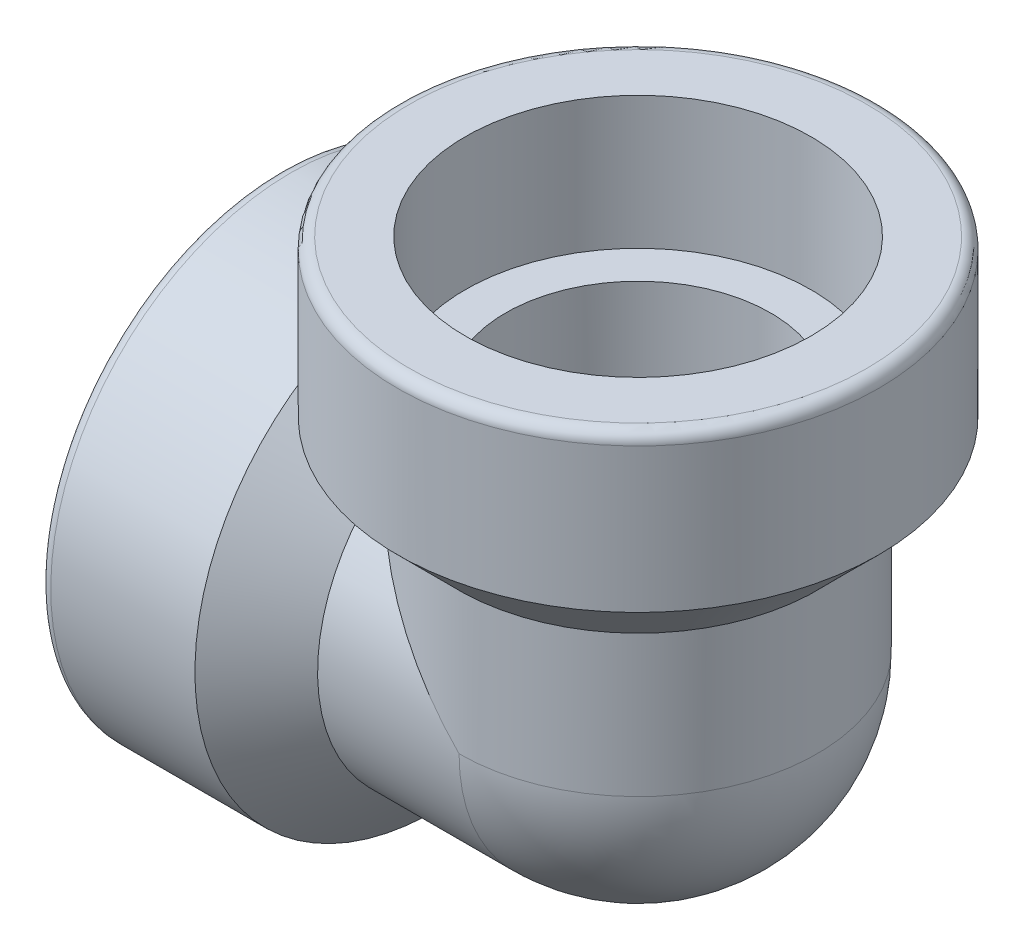
SolidWorks part; units mm, degrees
ref_plane "Front" through (0, 0, 0) normal (0, 0, 1) x (1, 0, 0)
ref_plane "Top" through (0, 0, 0) normal (0, 1, 0) x (1, 0, 0)
ref_plane "Right" through (0, 0, 0) normal (1, 0, 0) x (0, 0, -1)
sketch "Sketch1" plane through (0, 0, 0) normal (0, 0, 1) x (1, 0, 0)
  line L0 (0, 0) -> (0, 35.052) construction
  line L1 (0, 0) -> (-35.052, 0) construction
  line L2 (-35.052, 16.891) -> (-35.052, -16.891) construction
  line L3 (-16.891, 35.052) -> (16.891, 35.052) construction
  line L4 (-16.891, 22.098) -> (16.891, 22.098) construction
  line L5 (-22.098, 16.891) -> (-22.098, -16.891) construction
  line L6 (-16.891, 0) -> (16.891, 0) construction
  line L7 (0, 16.891) -> (0, -16.891) construction
  line L8 (23.495, 35.052) -> (-23.495, 35.052) construction
  line L9 (-35.052, 23.495) -> (-35.052, -23.495) construction
  dimension "D1" = 12.954
  dimension "D2" = 35.052
  dimension "D3" = 46.99
sketch "Sketch2" plane through (0, 0, 0) normal (0, 0, 1) x (1, 0, 0)
  line L0 (-35.052, -16.891) -> (-22.098, -16.891)
  line L1 (-22.098, -16.891) -> (-22.098, -12.954)
  line L2 (-22.098, 16.891) -> (-22.098, -16.891) construction
  line L3 (-22.098, -12.954) -> (0, -12.954)
  line L4 (0, 16.891) -> (0, -16.891) construction
  line L5 (0, 0) -> (-35.052, 0) construction
  line L6 (-35.052, -16.891) -> (-35.052, -22.3584)
  line L7 (-33.9153, -23.495) -> (-19.8247, -23.495)
  line L8 (-19.8247, -23.495) -> (-13.8303, -17.5006)
  line L9 (-13.8303, -17.5006) -> (0, -17.5006)
  line L10 (0, -17.5006) -> (0, -12.954)
  arc A0 (-35.052, -22.3584) -> (-33.9153, -23.495) centre (-33.9153, -22.3584) ccw
  point P19 (-35.052, -23.495)
  dimension "D3" = 1.1366
  dimension "D1" = 45
  dimension "w" = 4.5466
  dimension "D2" = 2.2733
revolve "Revolve1" add sketch "Sketch2" angle 360 about L5
sketch "Sketch9" plane through (0, 0, 0) normal (0, 0, 1) x (1, 0, 0)
  line L3 (-35.052, -16.891) -> (-22.098, -16.891)
  line L4 (-22.098, -16.891) -> (-22.098, -12.3444)
  line L5 (-22.098, -12.3444) -> (0, -12.3444)
  line L7 (-22.098, 12.3444) -> (-12.3444, 12.3444)
  line L8 (-22.098, 16.891) -> (-22.098, 12.3444)
  line L9 (-35.052, 16.891) -> (-22.098, 16.891)
  line L10 (16.891, 35.052) -> (16.891, 22.098)
  line L11 (16.891, 22.098) -> (12.3444, 22.098)
  line L12 (12.3444, 22.098) -> (12.3444, 0)
  line L13 (-16.891, 22.098) -> (-12.3444, 22.098)
  line L14 (-12.3444, 22.098) -> (-12.3444, 12.3444)
  line L15 (-16.891, 35.052) -> (-16.891, 22.098)
  line L19 (-16.891, 22.098) -> (16.891, 22.098) construction
  line L20 (-22.098, 16.891) -> (-22.098, -16.891) construction
  arc A1 (0, -12.3444) -> (12.3444, 0) centre (0, 0) ccw
  point P22 (0, 72.898)
  dimension "D1" = 4.5466
  dimension "D2" = 4.5466
sketch "Sketch3" plane through (0, 0, 0) normal (1, 0, 0) x (0, 0, -1)
  line L0 (0, 0) -> (23.495, 0) construction
  circle A0 centre (0, 0) radius 23.495 construction
ref_axis "Axis1" through (0, 0, -23.495) along (0, 0, 1)
pattern_circular "CirPattern2" count 2 over 90 about axis through (0, 0, -23.495) along (0, 0, 1)
sketch "Sketch4" plane through (0, 0, 0) normal (1, 0, 0) x (0, 0, -1)
  circle A0 centre (0, 0) radius 12.954 construction
  circle A1 centre (0, 0) radius 12.954
extrude "Cut-Extrude1" cut sketch "Sketch4" against normal through all
sketch "Sketch5" plane through (0, 0, 0) normal (0, -1, 0) x (1, 0, 0)
  circle A0 centre (0, 0) radius 12.954 construction
  circle A1 centre (0, 0) radius 12.954
extrude "Cut-Extrude2" cut sketch "Sketch5" against normal through all
combine bodies "Combine1" operation type add bodies to combine 105 104
sketch "Sketch6" plane through (0, 0, 0) normal (1, 0, 0) x (0, 0, -1)
  line L0 (0, 0) -> (23.495, 0) construction
  line L1 (-17.5006, 0) -> (-12.954, 0)
  line L2 (12.954, 0) -> (17.5006, 0)
  line L3 (-12.954, 0) -> (12.954, 0) construction
  arc A0 (-12.954, 0) -> (12.954, 0) centre (0, 0) ccw construction
  arc A1 (-17.5006, 0) -> (17.5006, 0) centre (0, 0) ccw construction
  arc A2 (-12.954, 0) -> (12.954, 0) centre (0, 0) ccw
  arc A3 (-17.5006, 0) -> (17.5006, 0) centre (0, 0) ccw
revolve "Revolve2" add sketch "Sketch6" angle 90 about L3
equation "\"D1@Sketch1\" = \"J@Sketch1\""
equation "\"D2@Sketch1\" = \"M@Sketch1\""
equation "\"D3@Sketch1\" = \"E@Sketch1\""
equation "\"D3@Sketch2\" = \"w@Sketch2\"/4"
equation "\"D2@Sketch2\" = \"w@Sketch2\"/2"
equation "\"D1@Sketch9\" = \"w@Sketch2\""
equation "\"D2@Sketch9\" = \"D1@Sketch9\""
